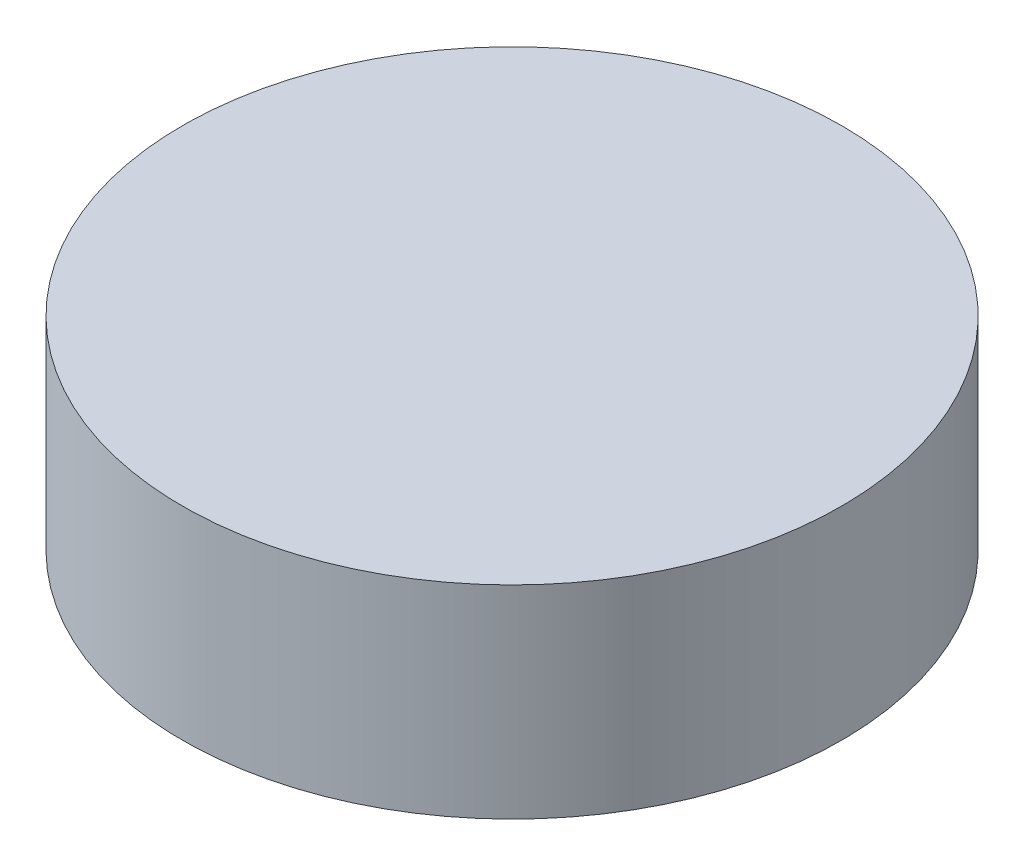
SolidWorks part; units mm, degrees
ref_plane "前视基准面" through (0, 0, 0) normal (0, 0, 1) x (1, 0, 0)
ref_plane "上视基准面" through (0, 0, 0) normal (0, 1, 0) x (1, 0, 0)
ref_plane "右视基准面" through (0, 0, 0) normal (1, 0, 0) x (0, 0, -1)
other "Configuration Table"
sketch "草图1" plane through (0, 0, 0) normal (0, 0, 1) x (1, 0, 0)
  line L0 (0, 0) -> (6.5, 0)
  line L1 (6.5, 0) -> (6.5, 4)
  line L2 (6.5, 4) -> (0, 4)
  line L3 (0, 4) -> (0, 0)
  line L4 (0, 0) -> (0, 4) construction
  dimension "radius" = 6.5
  dimension "height" = 4
revolve "Revolve" add sketch "草图1" angle 360 about L4
